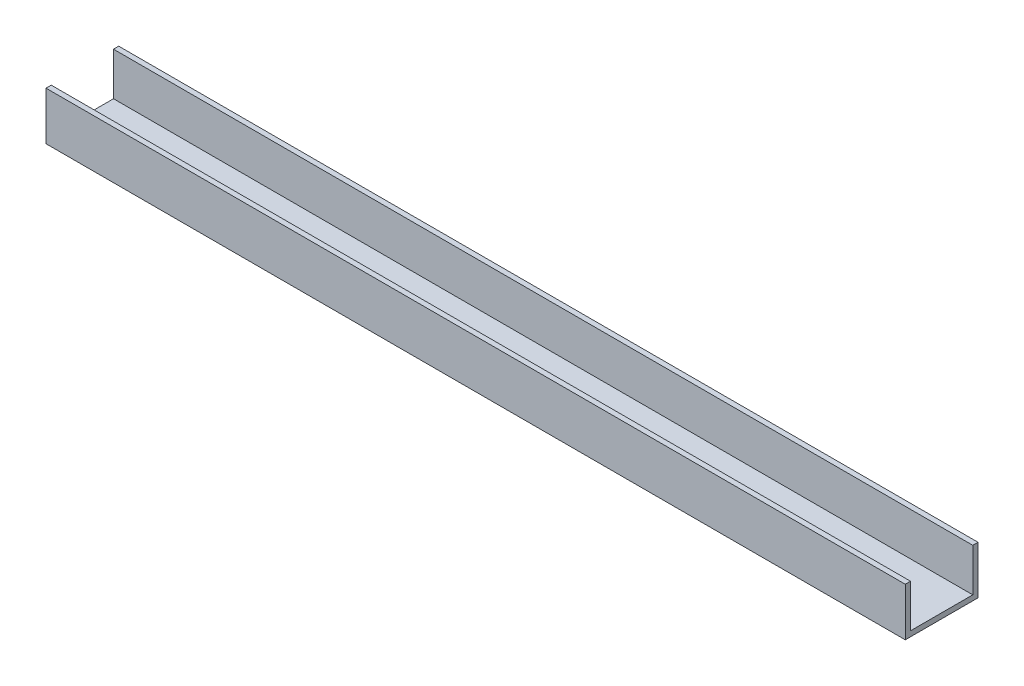
SolidWorks part; units mm, degrees
ref_plane "Front Plane" through (0, 0, 0) normal (0, 0, 1) x (1, 0, 0)
ref_plane "Top Plane" through (0, 0, 0) normal (0, 1, 0) x (1, 0, 0)
ref_plane "Right Plane" through (0, 0, 0) normal (1, 0, 0) x (0, 0, -1)
sketch "Sketch1" plane through (0, 0, 0) normal (1, 0, 0) x (0, 0, -1)
  line L0 (0, 0) -> (0, 1.6002) construction
  line L1 (9.525, 1.6002) -> (-9.525, 1.6002)
  line L2 (-9.525, 1.6002) -> (-9.525, 14.732)
  line L3 (-9.525, 14.732) -> (-11.1252, 14.732)
  line L4 (-11.1252, 14.732) -> (-11.1252, 0)
  line L5 (-11.1252, 0) -> (11.1252, 0)
  line L6 (9.525, 14.732) -> (11.1252, 14.732)
  line L7 (11.1252, 14.732) -> (11.1252, 0)
  line L8 (9.525, 1.6002) -> (9.525, 14.732)
  dimension "D1" = 1.6002
  dimension "D2" = 14.732
  dimension "D3" = 9.525
extrude "Boss-Extrude1" add sketch "Sketch1" along normal blind 262.89
sketch "Sketch2" plane through (0, 0, 0) normal (0, -1, 0) x (1, 0, 0)
  line L0 (131.445, 11.1252) -> (131.445, -11.1252) construction
  line L1 (262.89, 11.1252) -> (0, 11.1252) construction
  line L2 (262.89, -11.1252) -> (0, -11.1252) construction
  line L3 (0, 11.1252) -> (0, -11.1252) construction
  circle A0 centre (12.7, 0) radius 2.286
  circle A1 centre (250.19, 0) radius 2.286
  dimension "D2" = 4.572
  dimension "D1" = 12.7
extrude "Cut-Extrude1" [suppressed] cut sketch "Sketch2" against normal through all
chamfer "Chamfer1" [suppressed] distance 1.778 angle 49
